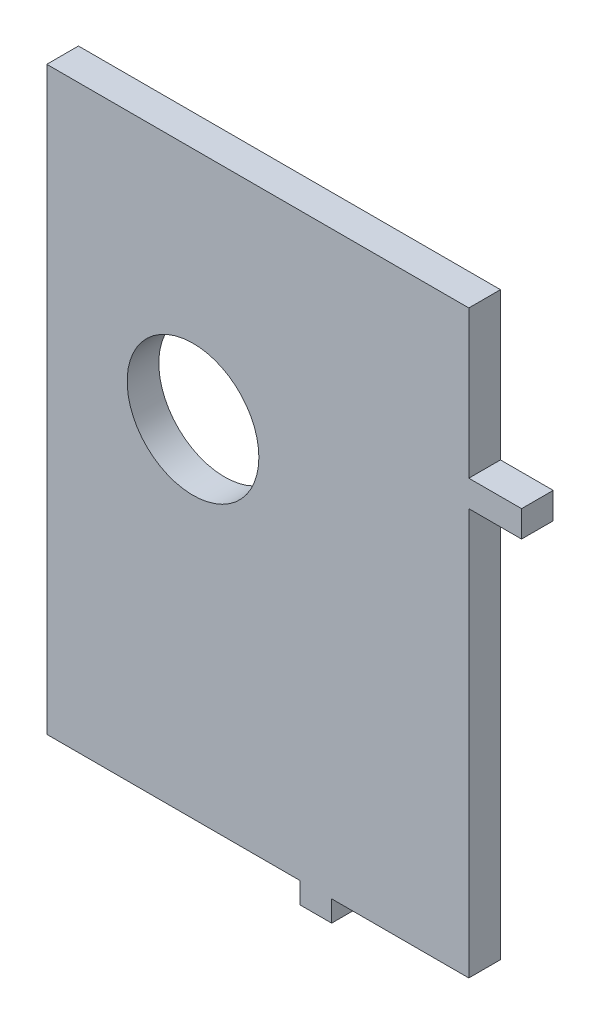
SolidWorks part; units mm, degrees
ref_plane "Front Plane" through (0, 0, 0) normal (0, 0, 1) x (1, 0, 0)
ref_plane "Top Plane" through (0, 0, 0) normal (0, 1, 0) x (1, 0, 0)
ref_plane "Right Plane" through (0, 0, 0) normal (1, 0, 0) x (0, 0, -1)
sketch "Sketch3" plane through (0, 0, 0) normal (0, 0, 1) x (1, 0, 0)
  line L1 (0, 0) -> (80, 0)
  line L2 (0, 0) -> (0, 110)
  line L3 (0, 110) -> (80, 110)
  line L4 (80, 0) -> (80, 110)
  dimension "D1" = 110
  dimension "D2" = 80
extrude "Boss-Extrude1" add sketch "Sketch3" along normal blind 6
sketch "Sketch4" plane through (0, 0, 6) normal (0, 0, 1) x (1, 0, 0)
  line L0 (0, 0) -> (80, 0) construction
  line L1 (48, 0) -> (54, 0)
  line L2 (48, 0) -> (48, -4)
  line L3 (48, -4) -> (54, -4)
  line L4 (54, 0) -> (54, -4)
  line L5 (0, 0) -> (0, -11.3754) construction
  line L6 (80, 0) -> (80, -8.8097) construction
  dimension "D1" = 48
  dimension "D2" = 26
  dimension "D3" = 4
extrude "Boss-Extrude2" add sketch "Sketch4" against normal up to vertex (6 mm away)
sketch "Sketch5" plane through (0, 0, 6) normal (0, 0, 1) x (1, 0, 0)
  line L0 (0, 0) -> (0, -8.6494) construction
sketch "Sketch6" plane through (0, 0, 6) normal (0, 0, 1) x (1, 0, 0)
  line L0 (80, 0) -> (80, 110) construction
  line L1 (80, 82.05) -> (90, 82.05)
  line L2 (80, 82.05) -> (80, 77.05)
  line L3 (80, 77.05) -> (90, 77.05)
  line L4 (90, 82.05) -> (90, 77.05)
  line L5 (80, 110) -> (116.6516, 110) construction
  dimension "D1" = 27.95
  dimension "D2" = 5
  dimension "D3" = 10
extrude "Boss-Extrude3" add sketch "Sketch6" against normal blind 6
sketch "Sketch7" plane through (0, 0, 6) normal (0, 0, 1) x (1, 0, 0)
  line L0 (80, 110) -> (107.6762, 110) construction
sketch "Sketch8" plane through (0, 0, 6) normal (0, 0, 1) x (1, 0, 0)
  line L0 (80, 82.05) -> (80, 110) construction
  line L1 (15.2359, 65.58) -> (15.2359, 128.1846) construction
  line L2 (80, 110) -> (0, 110) construction
  circle A0 centre (27.72, 65.58) radius 12.4841
  dimension "D1" = 24.9682
  dimension "D2" = 52.28
  dimension "D3" = 44.42
extrude "Cut-Extrude1" cut sketch "Sketch8" against normal blind 6
